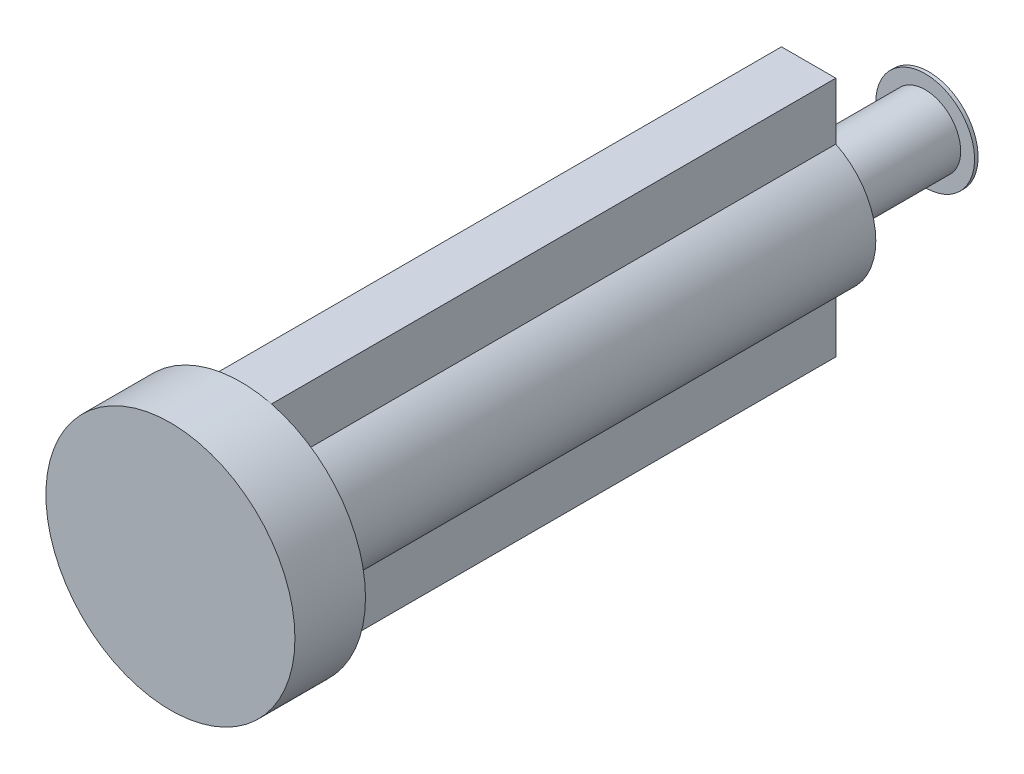
SolidWorks part; units mm, degrees
ref_plane "Front Plane" through (0, 0, 0) normal (0, 0, 1) x (1, 0, 0)
ref_plane "Top Plane" through (0, 0, 0) normal (0, 1, 0) x (1, 0, 0)
ref_plane "Right Plane" through (0, 0, 0) normal (1, 0, 0) x (0, 0, -1)
sketch "Sketch3" plane through (0, 0, 0) normal (0, 0, 1) x (1, 0, 0)
  line L0 (-3.3713, -9.4146) -> (-3.3713, -17.1146)
  line L1 (-3.3713, 17.1146) -> (4.3287, 17.1146)
  line L2 (-3.3713, 17.1146) -> (-3.3713, 9.4146)
  line L3 (-3.3713, -17.1146) -> (4.3287, -17.1146)
  line L4 (4.3287, 17.1146) -> (4.3287, 9.0146)
  line L5 (4.3287, -9.0146) -> (4.3287, -17.1146)
  arc A0 (-3.3713, 9.4146) -> (-3.3713, -9.4146) centre (0, 0) ccw
  arc A3 (4.3287, -9.0146) -> (4.3287, 9.0146) centre (0, 0) ccw
  dimension "D1" = 20
  dimension "D2" = 7.7
  dimension "D3" = 8.1
  dimension "D4" = 7.7
  dimension "D5" = 7.7
  dimension "D6" = 8.1
  dimension "D7" = 7.7
extrude "Boss-Extrude1" add sketch "Sketch3" along normal blind 80
sketch "Sketch4" plane through (0, 0, 80) normal (0, 0, 1) x (1, 0, 0)
  circle A0 centre (0, 0) radius 17.6535
extrude "Boss-Extrude2" add sketch "Sketch4" along normal blind 10
sketch "Sketch5" plane through (0, 0, 0) normal (0, 0, -1) x (-1, 0, 0)
  circle A0 centre (0, 0) radius 5.035
extrude "Boss-Extrude3" add sketch "Sketch5" along normal blind 17
sketch "Sketch9" plane through (0, 0, -17) normal (0, 0, -1) x (-1, 0, 0)
  circle A0 centre (0, 0) radius 7
  dimension "D1" = 14
extrude "Boss-Extrude6" add sketch "Sketch9" along normal blind 0.5
